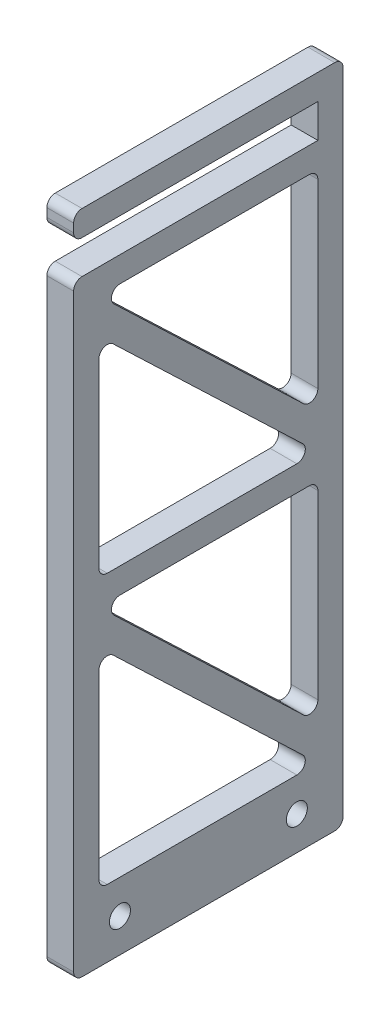
SolidWorks part; units mm, degrees
material "ABS"
ref_plane "Front Plane" through (0, 0, 0) normal (0, 0, 1) x (1, 0, 0)
ref_plane "Top Plane" through (0, 0, 0) normal (0, 1, 0) x (1, 0, 0)
ref_plane "Right Plane" through (0, 0, 0) normal (1, 0, 0) x (0, 0, -1)
sketch "Sketch1" plane through (0, 0, 0) normal (1, 0, 0) x (0, 0, -1)
  line L0 (16, -39.5) -> (-16, -39.5) construction
  line L1 (-16, 39.5) -> (16, 39.5)
  line L2 (-16, 39.5) -> (-16, -39.5)
  line L3 (-16, -39.5) -> (16, -39.5)
  line L4 (16, 39.5) -> (16, -39.5)
  line L5 (-16, 39.5) -> (16, -39.5) construction
  line L6 (-16, -39.5) -> (16, 39.5) construction
  point P0 (0, 0)
  dimension "D1" = 79
extrude "Boss-Extrude1" add sketch "Sketch1" along normal blind 3.175
sketch "Sketch2" plane through (3.175, 0, 0) normal (1, 0, 0) x (0, 0, -1)
  line L0 (-16, 39.5) -> (-16, -39.5) construction
  line L1 (-16, 36.5) -> (13, 36.5)
  line L2 (-16, 36.5) -> (-16, 32.5)
  line L3 (-16, 32.5) -> (13, 32.5)
  line L4 (13, 36.5) -> (13, 32.5)
  line L5 (16, -39.5) -> (16, 39.5) construction
  line L6 (16, 39.5) -> (-16, 39.5) construction
  point P6 (13, 34.5)
  dimension "D1" = 4
  dimension "D2" = 3
  dimension "D3" = 3
extrude "Cut-Extrude1" cut sketch "Sketch2" against normal up to surface (3.175 mm away) up to face at (0, 0, 0)
hole_wizard "Ø2.5mm Dowel Hole1" positions "Sketch4" profile "Sketch5" hole size "Ø2.5" standard "ANSI Metric" end condition up to next
sketch "Sketch4" plane through (0, 0, 0) normal (-1, 0, 0) x (0, 0, 1)
  line L0 (-16, -39.5) -> (-16, 39.5) construction
  line L1 (16, -39.5) -> (-16, -39.5) construction
  line L2 (16, 32.5) -> (16, -39.5) construction
  point P0 (-10.5, -35.5)
  point P2 (10.5, -35.5)
  dimension "D1" = 5.5
  dimension "D2" = 4
  dimension "D3" = 5.5
  dimension "D4" = 4
sketch "Sketch5" plane through (0, -35.5, -10.5) normal (0, 1, 0) x (0, 0, 1)
  line L0 (0, 0) -> (0, 3.175)
  line L1 (0, 3.175) -> (1.25, 3.175)
  line L2 (1.25, 3.175) -> (1.25, 0)
  line L5 (1.25, 0) -> (0, 0)
  line L11 (0, -6.35) -> (0, 107.95) construction
  dimension "Thru Hole Dia." = 2.5
  dimension "Thru Hole Depth" = 3.175
sketch "Sketch8" plane through (3.175, 0, 0) normal (1, 0, 0) x (0, 0, -1)
  line L0 (-13, -31.5) -> (13, -31.5)
  line L1 (13, -31.5) -> (-13, -6.6499)
  line L2 (-13, -6.6499) -> (-13, -31.5)
  line L3 (-13, -2.5) -> (13, -27.3501)
  line L4 (13, -27.3501) -> (13, -2.5)
  line L5 (13, -2.5) -> (-13, -2.5)
  line L6 (-13, 0.5) -> (13, 0.5)
  line L7 (13, 0.5) -> (-13, 25.3501)
  line L8 (-13, 25.3501) -> (-13, 0.5)
  line L9 (-13, 29.5) -> (13, 4.6499)
  line L10 (13, 4.6499) -> (13, 29.5)
  line L11 (13, 29.5) -> (-13, 29.5)
  line L12 (-16, 32.5) -> (-16, -39.5) construction
  line L13 (16, -39.5) -> (16, 39.5) construction
  line L14 (-16, 32.5) -> (13, 32.5) construction
  circle A0 centre (10.5, -35.5) radius 1.25 construction
  dimension "4" = 4
  dimension "D1" = 3
  dimension "D2" = 3
  dimension "D3" = 3
  dimension "D4" = 3
  dimension "D5" = 3
  dimension "D6" = 3
extrude "Cut-Extrude2" cut sketch "Sketch8" against normal up to surface (3.175 mm away) up to face at (0, 17.25, 0.75)
fillet "Fillet2" radius 1 6 edges at (1.5875, -39.5, -16) (1.5875, -39.5, 16) (1.5875, 32.5, 16) (1.5875, 36.5, 16) (1.5875, 39.5, 16) (1.5875, 39.5, -16)
fillet "Fillet3" radius 1 12 edges at (1.5875, -27.3501, -13) (1.5875, -2.5, -13) (1.5875, -31.5, -13) (1.5875, -6.6499, 13) (1.5875, -31.5, 13) (1.5875, 0.5, 13) (1.5875, 25.3501, 13) (1.5875, 0.5, -13) (1.5875, 4.6499, -13) (1.5875, 29.5, -13) (1.5875, 29.5, 13) (1.5875, -2.5, 13)
equation "\"BarWidth\"=3"
equation "\"D1@Sketch8\"=\"BarWidth\""
equation "\"D2@Sketch8\"=\"BarWidth\""
equation "\"D3@Sketch8\"=\"BarWidth\""
equation "\"D4@Sketch8\"=\"BarWidth\""
equation "\"D5@Sketch8\"=\"BarWidth\""
equation "\"D6@Sketch8\"=\"BarWidth\""
